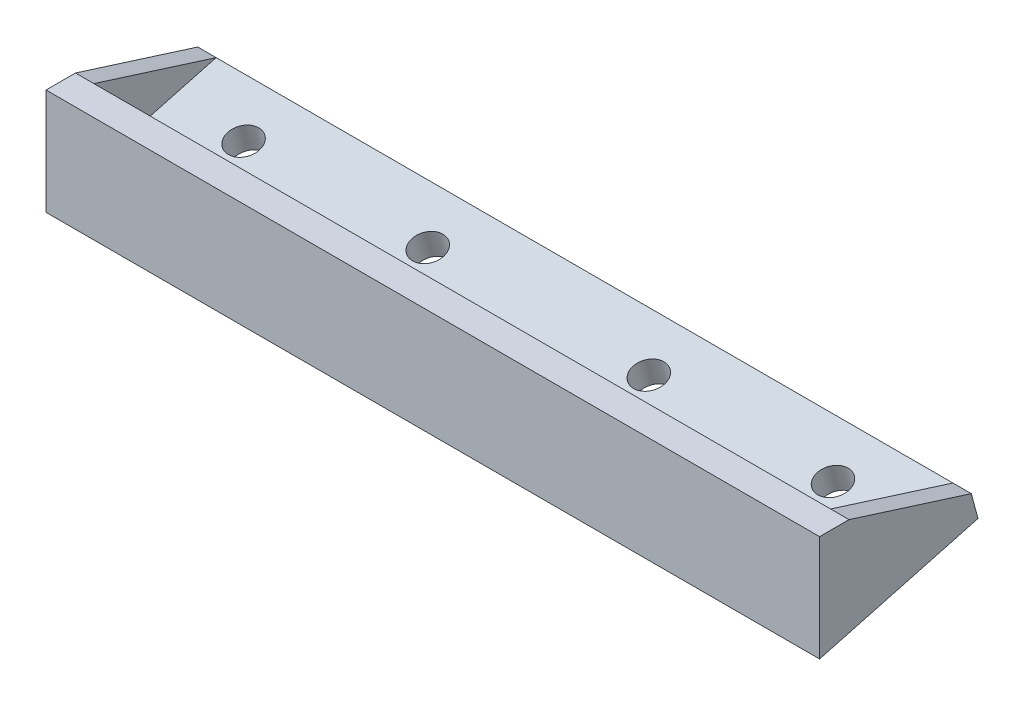
SolidWorks part; units mm, degrees
material "1060 合金"
ref_plane "前视基准面" through (0, 0, 0) normal (0, 0, 1) x (1, 0, 0)
ref_plane "上视基准面" through (0, 0, 0) normal (0, 1, 0) x (1, 0, 0)
ref_plane "右视基准面" through (0, 0, 0) normal (1, 0, 0) x (0, 0, -1)
sketch "草图1" plane through (0, 0, 0) normal (0, 1, 0) x (1, 0, 0)
  line L0 (0, 0) -> (170, 0) construction
  line L1 (170, 31.93) -> (170, -31.93)
  line L2 (15.8391, 73.3084) -> (162.1119, 41.7045)
  line L3 (15.8391, -73.3084) -> (162.1119, -41.7045)
  arc A0 (15.8391, 73.3084) -> (15.8391, -73.3084) centre (0, 0) ccw
  arc A1 (162.1119, -41.7045) -> (170, -31.93) centre (160, -31.93) ccw
  arc A2 (170, 31.93) -> (162.1119, 41.7045) centre (160, 31.93) ccw
  point P6 (170, 0)
  dimension "D1" = 150
  dimension "D4" = 20
  dimension "D5" = 20
  dimension "D2" = 170
  dimension "D3" = 63.86
extrude "凸台-拉伸1" add sketch "草图1" along normal blind 30
sketch "草图2" plane through (0, 30, 0) normal (0, 1, 0) x (1, 0, 0)
  circle A0 centre (0, 0) radius 44.45
  dimension "D1" = 88.9
extrude "切除-拉伸1" cut sketch "草图2" against normal blind 4
sketch "草图3" plane through (0, 26, 0) normal (0, 1, 0) x (1, 0, 0)
  line L0 (0, 0) -> (0, 90.3276) construction
  circle A0 centre (0, 0) radius 25.5
  circle A1 centre (0, 41) radius 2.25
  circle A2 centre (28.9914, 28.9914) radius 2.25
  circle A3 centre (41, 0) radius 2.25
  circle A4 centre (28.9914, -28.9914) radius 2.25
  circle A5 centre (0, -41) radius 2.25
  circle A6 centre (-28.9914, -28.9914) radius 2.25
  circle A7 centre (-41, 0) radius 2.25
  circle A8 centre (-28.9914, 28.9914) radius 2.25
  dimension "D1" = 51
  dimension "D3" = 4.5
  dimension "D2" = 41
  dimension "D4" = 8
extrude "切除-拉伸2" cut sketch "草图3" against normal through all contours A2 | A3 | A4 | A5 | A6 | A7 | A8 | A1 | A0
sketch "草图4" plane through (0, 30, 0) normal (0, 1, 0) x (1, 0, 0)
  line L0 (0, 0) -> (134, 0) construction
  line L1 (124, 18.5) -> (134, 18.5)
  line L2 (124, -18.5) -> (134, -18.5)
  arc A0 (134, -18.5) -> (134, 18.5) centre (134, 0) ccw
  arc A1 (124, 18.5) -> (124, -18.5) centre (124, 0) ccw
  dimension "D2" = 37
  dimension "D3" = 37
  dimension "D1" = 134
  dimension "D4" = 10
extrude "切除-拉伸3" cut sketch "草图4" against normal through all
sketch "草图5" plane through (0, 30, 0) normal (0, 1, 0) x (1, 0, 0)
  arc A0 (134, -18.5) -> (134, 18.5) centre (134, 0) ccw construction
  arc A1 (124, 18.5) -> (124, -18.5) centre (124, 0) ccw construction
  arc A2 (134, -18.5) -> (134, 18.5) centre (134, 0) ccw construction
  arc A3 (124, 18.5) -> (124, -18.5) centre (124, 0) ccw construction
  circle A4 centre (116.75, 25.5) radius 1.65
  circle A5 centre (141.25, 25.5) radius 1.65
  circle A6 centre (141.25, -25.5) radius 1.65
  circle A7 centre (116.75, -25.5) radius 1.65
  dimension "D1" = 3.3
  dimension "D2" = 3.3
  dimension "D3" = 3.3
  dimension "D4" = 3.3
  dimension "D7" = 25.5
  dimension "D5" = 7.25
  dimension "D6" = 25.5
  dimension "D8" = 7.25
  dimension "D9" = 7.25
extrude "切除-拉伸4" cut sketch "草图5" against normal through all
sketch "草图6" plane through (0, 30, 0) normal (0, 1, 0) x (1, 0, 0)
  line L0 (158, 42.5929) -> (158, -42.5929) construction
  line L2 (-52, 54.0463) -> (-52, -54.0463) construction
  line L6 (162.1119, 41.7045) -> (15.8391, 73.3084) construction
  line L7 (15.8391, -73.3084) -> (162.1119, -41.7045) construction
  line L8 (-52, 95) -> (-52, -95)
  line L9 (158, 95) -> (158, -95)
  line L10 (-52, 95) -> (158, 95)
  line L11 (-52, -95) -> (158, -95)
  line L15 (162.1119, 41.7045) -> (15.8391, 73.3084)
  line L16 (15.8391, -73.3084) -> (162.1119, -41.7045)
  line L17 (170, -31.93) -> (170, 31.93)
  line L18 (162.1119, 41.7045) -> (15.8391, 73.3084)
  line L19 (15.8391, -73.3084) -> (162.1119, -41.7045)
  line L20 (170, -31.93) -> (170, 31.93)
  arc A0 (15.8391, 73.3084) -> (15.8391, -73.3084) centre (0, 0) ccw construction
  arc A6 (170, 31.93) -> (162.1119, 41.7045) centre (160, 31.93) ccw
  arc A7 (15.8391, 73.3084) -> (15.8391, -73.3084) centre (0, 0) ccw
  arc A8 (162.1119, -41.7045) -> (170, -31.93) centre (160, -31.93) ccw
  arc A9 (170, 31.93) -> (162.1119, 41.7045) centre (160, 31.93) ccw
  arc A10 (15.8391, 73.3084) -> (15.8391, -73.3084) centre (0, 0) ccw
  arc A11 (162.1119, -41.7045) -> (170, -31.93) centre (160, -31.93) ccw
  point P8 (-52, 0)
  point P13 (158, 0)
  line M26 (162.1119, 41.7045) -> (15.8391, 73.3084)
  arc M27 (15.8391, 73.3084) -> (15.8391, -73.3084) centre (0, 0) ccw
  line M28 (15.8391, -73.3084) -> (162.1119, -41.7045)
  dimension "D3" = 190
  dimension "D1" = 210
  dimension "D2" = 52
  dimension "D4" = 190
  dimension "D5" = 0
extrude "凸台-拉伸2" add sketch "草图6" against normal blind 30 contours L10 L8 L9 M27 M26 | L8 L11 L9 M28 M27
sketch "草图7" plane through (0, 30, 0) normal (0, 1, 0) x (1, 0, 0)
  line L0 (-52, 54.0463) -> (-52, -54.0463)
  line L1 (158, 42.5929) -> (158, -42.5929)
  line L9 (162.1119, 41.7045) -> (158, 42.5929)
  line L10 (158, 42.5929) -> (158, 95)
  line L11 (158, 95) -> (-52, 95)
  line L12 (-52, 95) -> (-52, 54.0463)
  line L13 (-52, -54.0463) -> (-52, -95)
  line L14 (-52, -95) -> (158, -95)
  line L15 (158, -95) -> (158, -42.5929)
  line L16 (158, -42.5929) -> (162.1119, -41.7045)
  line L17 (170, -31.93) -> (170, 31.93)
  line L18 (162.1119, 41.7045) -> (158, 42.5929)
  line L21 (-52, 95) -> (-52, 54.0463)
  line L25 (158, -42.5929) -> (162.1119, -41.7045)
  line L26 (170, -31.93) -> (170, 31.93)
  arc A3 (170, 31.93) -> (162.1119, 41.7045) centre (160, 31.93) ccw
  arc A4 (-52, 54.0463) -> (-52, -54.0463) centre (0, 0) ccw
  arc A5 (162.1119, -41.7045) -> (170, -31.93) centre (160, -31.93) ccw
  arc A6 (170, 31.93) -> (162.1119, 41.7045) centre (160, 31.93) ccw
  arc A7 (-52, 54.0463) -> (-52, -54.0463) centre (0, 0) ccw
  arc A8 (162.1119, -41.7045) -> (170, -31.93) centre (160, -31.93) ccw
  arc M22 (170, 31.93) -> (162.1119, 41.7045) centre (160, 31.93) ccw
  line M23 (162.1119, 41.7045) -> (158, 42.5929)
  arc M27 (-52, 54.0463) -> (-52, -54.0463) centre (0, 0) ccw
  line M31 (158, -42.5929) -> (162.1119, -41.7045)
  arc M32 (162.1119, -41.7045) -> (170, -31.93) centre (160, -31.93) ccw
  line M33 (170, -31.93) -> (170, 31.93)
  dimension "D1" = 0
extrude "切除-拉伸5" cut sketch "草图7" against normal through all contours L0 M27 | L1 M23 M31 M32 M33 M22
sketch "草图9" plane through (-52, 0, 0) normal (-1, 0, 0) x (0, 0, 1)
  line L0 (-95, 20) -> (-60, 10.6218)
  line L1 (-95, 30) -> (95, 30) construction
  line L3 (-60, 10.6218) -> (-60, 30)
  line L5 (-95, 0) -> (-95, 30) construction
  line L7 (-95, 20) -> (-95, 30)
  line L8 (-95, 30) -> (-60, 30)
  dimension "D1" = 15
  dimension "D3" = 19.3782
  dimension "D4" = 35
  dimension "D5" = 10
extrude "切除-拉伸7" cut sketch "草图9" against normal through all contours L8 L3 L0 L7
sketch "草图8" plane through (-52, 0, 0) normal (-1, 0, 0) x (0, 0, 1)
  line L0 (0, 0) -> (52, 0)
  line L1 (-95, 0) -> (95, 0) construction
  line L2 (52, 0) -> (52, 17.3)
  line L3 (52, 17.3) -> (-52, 17.3)
  line L4 (-52, 17.3) -> (-52, 0)
  line L5 (-52, 0) -> (0, 0)
  line L6 (-60, 30) -> (95, 30) construction
  dimension "D1" = 52
  dimension "D2" = 52
  dimension "D3" = 12.7
sketch "草图10" plane through (-52, 0, 0) normal (-1, 0, 0) x (0, 0, 1)
  line L0 (-95, 12.7531) -> (-47.4049, 0) construction
  line L1 (-95, 0) -> (-95, 20) construction
  line L2 (-95, 0) -> (95, 0) construction
  line L3 (-95, 20) -> (-60, 10.6218) construction
  line L6 (-95, 12.7531) -> (-52, 1.2313)
  line L7 (-52, 1.2313) -> (-52, 0)
  line L8 (-95, 12.7531) -> (-95, 0)
  line L9 (-95, 0) -> (-52, 0)
  line L10 (-52, 17.3) -> (-52, 0) construction
  dimension "D1" = 7
extrude "切除-拉伸8" cut sketch "草图10" against normal through all
extrude "切除-拉伸9" cut sketch "草图8" against normal through all
fillet "圆角1" radius 5 1 edges at (53, 10.6218, -60)
sketch "草图11" plane through (-52, 0, 0) normal (-1, 0, 0) x (0, 0, 1)
  line L0 (-95, 12.7531) -> (-93.1883, 19.5145)
  line L1 (-95, 20) -> (-66.2941, 12.3083) construction
  line L2 (-93.1883, 19.5145) -> (-95, 20)
  line L3 (-95, 20) -> (-95, 12.7531)
extrude "切除-拉伸10" cut sketch "草图11" against normal through all
sketch "草图12" plane through (-52, 0, 0) normal (-1, 0, 0) x (0, 0, 1)
  line L0 (-93.1883, 19.5145) -> (-60, 30)
  line L10 (-93.1883, 19.5145) -> (-95, 12.7531)
  line L11 (-95, 12.7531) -> (-52, 1.2313)
  line L12 (-52, 1.2313) -> (-52, 17.3)
  line L13 (-52, 17.3) -> (52, 17.3)
  line L14 (52, 17.3) -> (52, 0)
  line L15 (52, 0) -> (95, 0)
  line L16 (95, 0) -> (95, 30)
  line L17 (95, 30) -> (-60, 30)
  line L18 (-60, 30) -> (-60, 17.1379)
  line L19 (-66.2941, 12.3083) -> (-93.1883, 19.5145)
  line L28 (-60, 30) -> (-60, 17.1379)
  line L29 (-66.2941, 12.3083) -> (-93.1883, 19.5145)
  arc A1 (-66.2941, 12.3083) -> (-60, 17.1379) centre (-65, 17.1379) ccw
  arc A2 (-66.2941, 12.3083) -> (-60, 17.1379) centre (-65, 17.1379) ccw
  dimension "D1" = 0
extrude "凸台-拉伸3" add sketch "草图12" against normal blind 5
sketch "草图13" plane through (158, 0, 0) normal (1, 0, 0) x (0, 0, -1)
  line L3 (66.2941, 12.3083) -> (93.1883, 19.5145)
  line L4 (93.1883, 19.5145) -> (60, 30)
  line L5 (60, 30) -> (60, 17.1379)
  line L6 (66.2941, 12.3083) -> (93.1883, 19.5145)
  line L7 (93.1883, 19.5145) -> (60, 30)
  line L8 (60, 30) -> (60, 17.1379)
  arc A1 (60, 17.1379) -> (66.2941, 12.3083) centre (65, 17.1379) ccw
  arc A2 (60, 17.1379) -> (66.2941, 12.3083) centre (65, 17.1379) ccw
  dimension "D1" = 0
extrude "凸台-拉伸4" add sketch "草图13" against normal blind 5
sketch "草图14" plane through (0, -5.0897, -1.3638) normal (0, 0.9659, 0.2588) x (1, 0, 0)
  line L0 (153, 67.2208) -> (153, 95.0637) construction
  line L3 (153, 95.0637) -> (-47, 95.0637) construction
  circle A0 centre (-27, 82.0637) radius 4.25
  circle A1 centre (23, 82.0637) radius 4.25
  circle A2 centre (83, 82.0637) radius 4.25
  circle A3 centre (133, 82.0637) radius 4.25
  dimension "D1" = 8.5
  dimension "D2" = 160
  dimension "D3" = 20
  dimension "D4" = 50
  dimension "D5" = 50
  dimension "D6" = 13
extrude "切除-拉伸11" cut sketch "草图14" against normal through all
sketch "草图16" plane through (-52, 0, 0) normal (-1, 0, 0) x (0, 0, 1)
  line L0 (-60, 30) -> (95, 30) construction
  line L1 (95, 0) -> (52, 0)
  line L2 (95, 0) -> (95, 30)
  line L3 (95, 30) -> (52, 30)
  line L4 (52, 0) -> (52, 30)
extrude "切除-拉伸12" cut sketch "草图16" against normal through all
ref_plane "基准面1" through (0, -11.8512, -3.1755) normal (0, -0.9659, -0.2588) x (-1, 0, 0)
sketch "草图18" plane through (0, 30, 0) normal (0, 1, 0) x (1, 0, 0)
  line L1 (-52, -52) -> (158, -52)
  line L2 (-52, -52) -> (-52, -57)
  line L3 (-52, -57) -> (158, -57)
  line L4 (158, -52) -> (158, -57)
  dimension "D1" = 5
extrude "凸台-拉伸7" add sketch "草图18" against normal up to surface (56.6355 mm away) up to plane "基准面1"
sketch "草图19" plane through (-52, 0, 0) normal (-1, 0, 0) x (0, 0, 1)
  line L0 (57, -27.9752) -> (90.1883, -36.868)
  line L1 (90.1883, -36.868) -> (92, -30.1065)
  line L2 (92, -30.1065) -> (57, -20.7283)
  line L3 (57, -27.9752) -> (57, 30) construction
  line L4 (57, -20.7283) -> (57, -27.9752)
  line L5 (52, -26.6355) -> (57, -27.9752) construction
  dimension "D1" = 7
  dimension "D2" = 40
extrude "凸台-拉伸8" add sketch "草图19" against normal up to surface (210 mm away) up to face at (158, 8.1654, -14.9098)
sketch "草图20" plane through (-52, 0, 0) normal (-1, 0, 0) x (0, 0, 1)
  line L0 (92, -30.1065) -> (57, -20.7283) construction
  line L1 (57, -20.7283) -> (57, 30) construction
  line L2 (92, -30.1065) -> (57, -20.7283)
  line L3 (57, -20.7283) -> (57, 30)
  line L4 (57, 30) -> (92, -30.1065)
extrude "凸台-拉伸9" add sketch "草图20" against normal blind 5
sketch "草图21" plane through (158, 0, 0) normal (1, 0, 0) x (0, 0, -1)
  line L3 (-57, 30) -> (-92, -30.1065)
  line L4 (-92, -30.1065) -> (-57, -20.7283)
  line L5 (-57, -20.7283) -> (-57, 30)
  line L6 (-57, 30) -> (-92, -30.1065)
  line L7 (-92, -30.1065) -> (-57, -20.7283)
  line L8 (-57, -20.7283) -> (-57, 30)
  dimension "D1" = 0
extrude "凸台-拉伸10" add sketch "草图21" against normal blind 5
sketch "草图22" plane through (0, -5.0897, -1.3638) normal (0, 0.9659, 0.2588) x (1, 0, 0)
  line L0 (-47, -96.6573) -> (-47, -47.2932) construction
  line L2 (153, -96.6573) -> (153, -60.4226) construction
  circle A0 centre (-27, -77.9363) radius 4.25
  circle A1 centre (23, -69.9363) radius 4.25
  circle A2 centre (83, -69.9363) radius 4.25
  circle A3 centre (133, -77.9363) radius 4.25
  circle A4 centre (133, 82.0637) radius 4.25 construction
  circle A5 centre (-27, 82.0637) radius 4.25 construction
  circle A6 centre (23, 82.0637) radius 4.25 construction
  circle A7 centre (83, 82.0637) radius 4.25 construction
  dimension "D1" = 8.5
  dimension "D7" = 152
  dimension "D6" = 152
  dimension "D8" = 50
  dimension "D4" = 160
  dimension "D5" = 160
  dimension "D2" = 20
  dimension "D3" = 20
  dimension "D9" = 50
extrude "切除-拉伸13" cut sketch "草图22" against normal through all
fillet "圆角2" radius 5 1 edges at (53, -20.7283, 57)
sketch "草图23" plane through (-52, 0, 0) normal (-1, 0, 0) x (0, 0, 1)
  line L0 (-52, 17.3) -> (-52, 40.5241)
  line L1 (-52, 17.3) -> (-52, -43.9123)
  line L2 (-52, -43.9123) -> (98.6729, -43.9123)
  line L3 (98.6729, -43.9123) -> (98.6729, 40.5241)
  line L4 (98.6729, 40.5241) -> (-52, 40.5241)
extrude "切除-拉伸14" cut sketch "草图23" against normal through all
